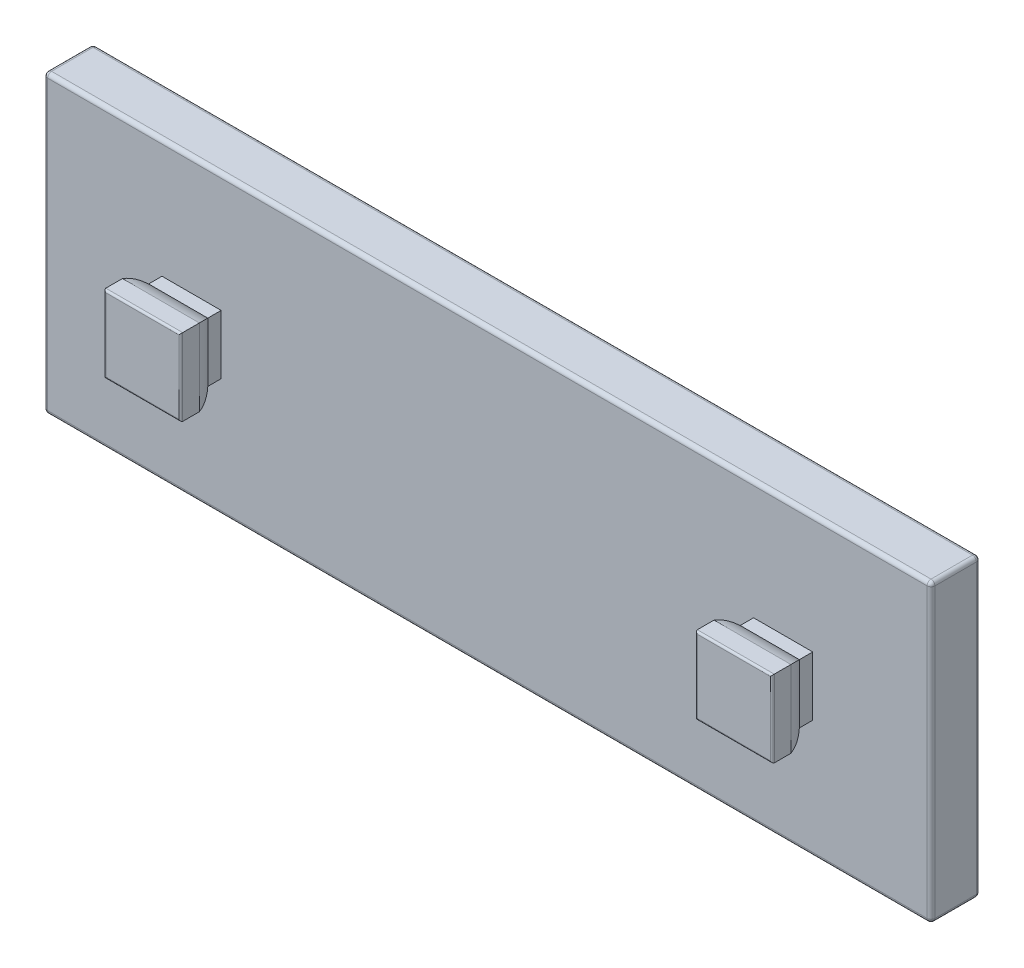
SolidWorks part; units mm, degrees
ref_plane "前视基准面" through (0, 0, 0) normal (0, 0, 1) x (1, 0, 0)
ref_plane "上视基准面" through (0, 0, 0) normal (0, 1, 0) x (1, 0, 0)
ref_plane "右视基准面" through (0, 0, 0) normal (1, 0, 0) x (0, 0, -1)
sketch "草图1" plane through (0, 0, 0) normal (0, 0, 1) x (1, 0, 0)
  line L1 (-22.5, -7.5) -> (22.5, -7.5)
  line L2 (-22.5, -7.5) -> (-22.5, 7.5)
  line L3 (-22.5, 7.5) -> (22.5, 7.5)
  line L4 (22.5, -7.5) -> (22.5, 7.5)
extrude "凸台-拉伸1" add sketch "草图1" against normal blind 2.5
sketch "草图2" plane through (0, 0, 0) normal (0, 0, 1) x (1, 0, 0)
  line L1 (-16.5, -1.5) -> (-13.5, -1.5)
  line L2 (-16.5, -1.5) -> (-16.5, 1.5)
  line L3 (-16.5, 1.5) -> (-13.5, 1.5)
  line L4 (-13.5, -1.5) -> (-13.5, 1.5)
  line L5 (13.5, 1.5) -> (16.5, 1.5)
  line L6 (13.5, 1.5) -> (13.5, -1.5)
  line L7 (13.5, -1.5) -> (16.5, -1.5)
  line L8 (16.5, 1.5) -> (16.5, -1.5)
extrude "凸台-拉伸2" add sketch "草图2" along normal blind 1
sketch "草图3" plane through (0, 0, 0) normal (0, 1, 0) x (1, 0, 0)
  line L0 (-16.95, -2.5) -> (-13.05, -2.5)
  line L1 (-16.95, -2.5) -> (-16.95, -1.5556)
  line L2 (-13.05, -2.5) -> (-13.05, -1.5556)
  line L3 (0, -3.2263) -> (0, 2.8368) construction
  line L4 (-16.5, -1) -> (-16.5, 0) construction
  line L5 (-16.5, -0.6771) -> (-13.5, -0.6771)
  line L6 (16.5, -0.6771) -> (13.5, -0.6771)
  line L7 (13.05, -2.5) -> (13.05, -1.5556)
  line L8 (16.95, -2.5) -> (16.95, -1.5556)
  line L9 (16.95, -2.5) -> (13.05, -2.5)
  arc A0 (-16.5, -0.6771) -> (-16.95, -1.5556) centre (-15, -2) ccw
  arc A1 (13.05, -1.5556) -> (13.5, -0.6771) centre (15, -2) cw
  arc A2 (-13.05, -1.5556) -> (-13.5, -0.6771) centre (-15, -2) ccw
  arc A3 (16.5, -0.6771) -> (16.95, -1.5556) centre (15, -2) cw
  dimension "D1" = 0.5
extrude "凸台-拉伸3" add sketch "草图3" along normal blind 2 and the other way blind 2
sketch "草图4" plane through (-16.95, 0, 0) normal (-1, 0, 0) x (0, 0, 1)
  line L0 (2.5, 1.95) -> (1.5556, 1.95)
  line L1 (0.6771, -2) -> (2.5, -2)
  line L2 (0.6771, -2) -> (0.6771, -1.5)
  line L3 (0.6771, 2) -> (2.5, 2)
  line L4 (2.5, -2) -> (2.5, -1.95)
  line L5 (2.5, -1.95) -> (1.5556, -1.95)
  line L7 (2.5, 1.95) -> (2.5, 2)
  line L8 (0.6771, 1.5) -> (0.6771, 2)
  arc A0 (1.5556, 1.95) -> (0.6771, 1.5) centre (2, 0) ccw
  arc A1 (0.6771, -1.5) -> (1.5556, -1.95) centre (2, 0) ccw
extrude "切除-拉伸1" cut sketch "草图4" against normal through all
fillet "圆角1" radius 0.2 12 edges at (0, -7.5, -2.5) (0, -7.5, 0) (-22.5, -7.5, -1.25) (-22.5, 0, -2.5) (-22.5, 0, 0) (-22.5, 7.5, -1.25) (0, 7.5, -2.5) (0, 7.5, 0) (22.5, 7.5, -1.25) (22.5, 0, -2.5) (22.5, -7.5, -1.25) (22.5, 0, 0)
fillet "圆角2" radius 0.1 8 edges at (13.05, 0, 2.5) (15, 1.95, 2.5) (16.95, 0, 2.5) (15, -1.95, 2.5) (-16.95, 0, 2.5) (-15, 1.95, 2.5) (-13.05, 0, 2.5) (-15, -1.95, 2.5)
sketch "草图6" plane through (0, 0, 0) normal (0, 1, 0) x (1, 0, 0)
  line L0 (0, 0) -> (0, 2.5) construction
  line L1 (-22.3, 2.5) -> (22.3, 2.5) construction
  line L2 (0, 2.5) -> (-7.5, 2.5) construction
  line L3 (-6, 2.5) -> (-9, 2.5)
  line L4 (-9, 2.5) -> (-9, 3.1771)
  line L5 (-7.5, 2.5) -> (-7.5, 4.5) construction
  line L6 (-7.5, 4.5) -> (-7.5, 5) construction
  line L7 (-5.55, 5) -> (-9.45, 5)
  line L8 (-9.45, 5) -> (-9.45, 4.0556)
  line L9 (-6, 2.5) -> (-6, 3.1771)
  line L10 (-5.55, 5) -> (-5.55, 4.0556)
  arc A0 (-9.45, 4.0556) -> (-9, 3.1771) centre (-7.5, 4.5) ccw
  arc A1 (-5.55, 4.0556) -> (-6, 3.1771) centre (-7.5, 4.5) cw
  dimension "D1" = 7.5
  dimension "D2" = 1.5
  dimension "D3" = 2
  dimension "D4" = 0.5
  dimension "D5" = 1.95
extrude "凸台-拉伸4" add sketch "草图6" along normal blind 2 and the other way blind 2
sketch "草图7" plane through (0, 0, 0) normal (1, 0, 0) x (0, 0, -1)
  line L0 (0, 0) -> (2.5, 0) construction
  line L1 (2.5, -2) -> (2.5, 2) construction
  line L2 (2.5, 0) -> (4.5, 0) construction
  line L3 (4.5, 0) -> (5, 0) construction
  line L4 (5, -2) -> (5, 2) construction
  line L5 (2.5, 0) -> (2.5, 1.5) construction
  line L6 (2.5, 1.5) -> (3.1771, 1.5)
  line L7 (5, 0) -> (5, 1.95) construction
  line L8 (5, 1.95) -> (4.0556, 1.95)
  line L10 (2.5, 1.5) -> (2.5, 2)
  line L11 (2.5, 2) -> (5, 2)
  line L12 (5, 2) -> (5, 1.95)
  line L13 (5, -1.95) -> (4.0556, -1.95)
  line L14 (2.5, -1.5) -> (3.1771, -1.5)
  line L15 (2.5, -1.5) -> (2.5, -2)
  line L16 (2.5, -2) -> (5, -2)
  line L17 (5, -2) -> (5, -1.95)
  arc A0 (4.0556, 1.95) -> (3.1771, 1.5) centre (4.5, 0) ccw
  arc A1 (4.0556, -1.95) -> (3.1771, -1.5) centre (4.5, 0) cw
  dimension "D4" = 2
  dimension "D1" = 2
  dimension "D2" = 1.5
  dimension "D3" = 1.95
extrude "切除-拉伸2" cut sketch "草图7" against normal blind 10
mirror "镜向1" about plane through (0, 0, 0) normal (1, 0, 0) of "切除-拉伸2", "凸台-拉伸4"
fillet "圆角3" radius 0.1 8 edges at (-9.45, 0, -5) (-7.5, -1.95, -5) (-5.55, 0, -5) (-7.5, 1.95, -5) (5.55, 0, -5) (7.5, -1.95, -5) (9.45, 0, -5) (7.5, 1.95, -5)
